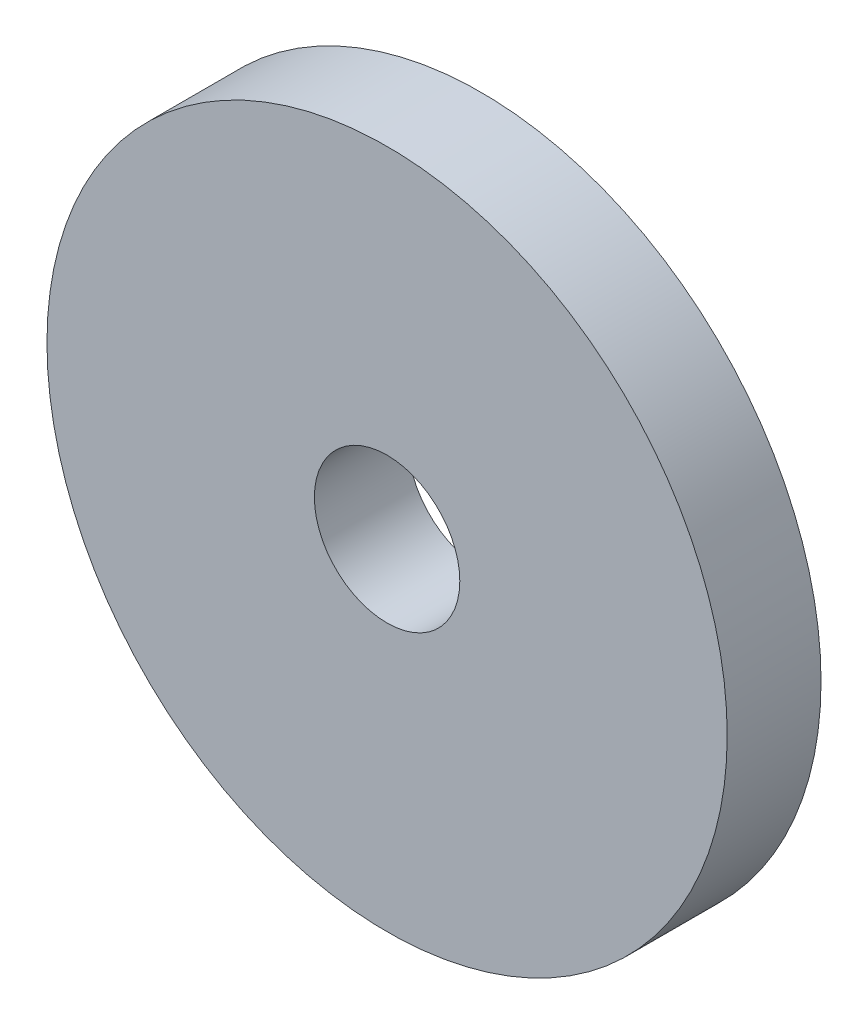
SolidWorks part; units mm, degrees
ref_plane "Front Plane" through (0, 0, 0) normal (0, 0, 1) x (1, 0, 0)
ref_plane "Top Plane" through (0, 0, 0) normal (0, 1, 0) x (1, 0, 0)
ref_plane "Right Plane" through (0, 0, 0) normal (1, 0, 0) x (0, 0, -1)
sketch "Sketch1" plane through (0, 0, 0) normal (0, 0, 1) x (1, 0, 0)
  circle A0 centre (0, 0) radius 7.25
  dimension "D1" = 14.5
extrude "Boss-Extrude1" add sketch "Sketch1" along normal blind 2
sketch "Sketch4" plane through (0, 0, 0) normal (0, 0, -1) x (-1, 0, 0)
  circle A0 centre (0, 0) radius 1.55
  dimension "D1" = 3.1
extrude "Cut-Extrude4" cut sketch "Sketch4" against normal blind 4.5
